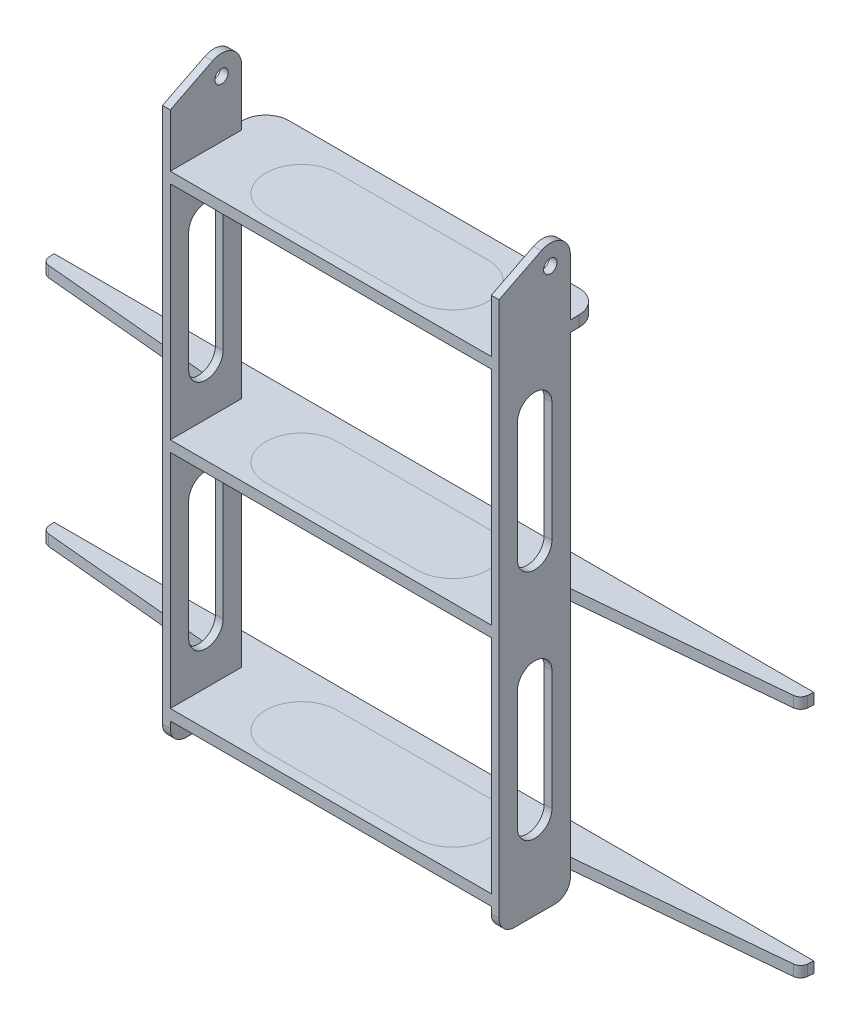
SolidWorks part; units mm, degrees
ref_plane "Front Plane" through (0, 0, 0) normal (0, 0, 1) x (1, 0, 0)
ref_plane "Top Plane" through (0, 0, 0) normal (0, 1, 0) x (1, 0, 0)
ref_plane "Right Plane" through (0, 0, 0) normal (1, 0, 0) x (0, 0, -1)
sketch "Sketch1" plane through (0, 0, 0) normal (0, 0, 1) x (1, 0, 0)
  line L1 (618.735, 7) -> (-618.735, 7)
  line L2 (618.735, 7) -> (618.735, -7)
  line L3 (618.735, -7) -> (-618.735, -7)
  line L4 (-618.735, 7) -> (-618.735, -7)
  line L5 (618.735, 7) -> (-618.735, -7) construction
  line L6 (618.735, -7) -> (-618.735, 7) construction
  point P0 (0, 0)
  dimension "D1" = 14
  dimension "D2" = 1237.47
extrude "Boss-Extrude1" add sketch "Sketch1" along normal blind 133
pattern_linear "LPattern1" count 3 spacing 300 along (0, -1, 0) of bodies 101
sketch "Sketch2" plane through (0, 7, 0) normal (0, 1, 0) x (1, 0, 0)
  line L0 (-675.1748, 0) -> (-675.1748, -133)
  line L1 (-675.1748, -133) -> (-217.0071, -133)
  line L2 (-217.0071, -133) -> (-217.0071, -41.0381)
  line L3 (-217.0071, -41.0381) -> (-488.6419, -15.7437)
  line L4 (-488.6419, -15.7437) -> (-489.975, 0)
  line L5 (-489.975, 0) -> (-675.1748, 0)
  line L6 (618.735, 0) -> (-618.735, 0) construction
  line L7 (618.735, -133) -> (-618.735, -133) construction
  line L8 (-618.735, -133) -> (-618.735, 0) construction
  line L9 (0, 0) -> (0, -201.9919) construction
  line L10 (489.975, 0) -> (675.1748, 0)
  line L11 (488.6419, -15.7437) -> (489.975, 0)
  line L12 (217.0071, -41.0381) -> (488.6419, -15.7437)
  line L13 (217.0071, -133) -> (217.0071, -41.0381)
  line L14 (675.1748, -133) -> (217.0071, -133)
  line L15 (675.1748, 0) -> (675.1748, -133)
  dimension "D1" = 94.84
  dimension "D2" = 100.16
  dimension "D3" = 128.76
  dimension "D4" = 15.8
  dimension "D5" = 272.81
  dimension "D6" = 401.7279
extrude "Cut-Extrude1" cut sketch "Sketch2" against normal through all both and the other way through all
sketch "Sketch3" plane through (-217.0071, 0, 0) normal (-1, 0, 0) x (0, 0, 1)
  line L0 (41.0381, -307) -> (41.0381, -293) construction
  line L1 (41.0381, 105.76) -> (133, 105.76)
  line L2 (41.0381, 105.76) -> (41.0381, -635.5)
  line L3 (41.0381, -635.5) -> (133, -635.5)
  line L4 (133, 105.76) -> (133, -635.5)
  line L5 (133, -293) -> (133, -307) construction
  line L6 (41.0381, 7) -> (133, 7) construction
  line L7 (133, -607) -> (41.0381, -607) construction
  dimension "D1" = 98.76
  dimension "D2" = 28.5
extrude "Boss-Extrude2" add sketch "Sketch3" against normal blind 10
mirror "Mirror1" about plane through (0, 0, 0) normal (1, 0, 0) of "Boss-Extrude2"
sketch "Sketch4" plane through (0, 7, 0) normal (0, 1, 0) x (1, 0, 0)
  line L0 (-217.0071, -133) -> (-217.0071, -41.0381) construction
  line L1 (-217.0071, 143.9317) -> (-506.9137, 143.9317)
  line L2 (-217.0071, 143.9317) -> (-217.0071, -232.2022)
  line L3 (-217.0071, -232.2022) -> (-506.9137, -232.2022)
  line L4 (-506.9137, 143.9317) -> (-506.9137, -232.2022)
  line L5 (0, -174.1148) -> (0, -390.7884) construction
  line L6 (217.0071, -232.2022) -> (506.9137, -232.2022)
  line L7 (506.9137, 143.9317) -> (506.9137, -232.2022)
  line L8 (217.0071, 143.9317) -> (506.9137, 143.9317)
  line L9 (217.0071, 143.9317) -> (217.0071, -232.2022)
  point P13 (0, -174.1148)
extrude "Cut-Extrude3" cut sketch "Sketch4" against normal blind 105
sketch "Sketch5" plane through (217.0071, 0, 0) normal (1, 0, 0) x (0, 0, -1)
  line L0 (-41.0381, -7) -> (-41.0381, -293) construction
  line L1 (-133, 105.76) -> (-41.0381, 105.76) construction
  line L2 (-133, 75.48) -> (-78.5502, 102.9795)
  line L3 (-66.8981, 79.9) -> (-78.5502, 102.9795) construction
  line L4 (-133, -635.5) -> (-133, 105.76) construction
  line L5 (-41.0381, 105.76) -> (-41.0381, 7) construction
  line L6 (-66.8981, 79.9) -> (-41.0381, 79.9) construction
  line L7 (-133, 75.48) -> (-161.3031, 75.48)
  line L8 (-161.3031, 75.48) -> (-161.3031, 131.4565)
  line L9 (-161.3031, 131.4565) -> (-29.3032, 131.4565)
  line L10 (-29.3032, 131.4565) -> (-29.3032, 79.9)
  line L11 (-29.3032, 79.9) -> (-41.0381, 79.9)
  circle A0 centre (-66.8981, 79.9) radius 8.65
  arc A1 (-78.5502, 102.9795) -> (-41.0381, 79.9) centre (-66.8941, 79.9) cw
  point P11 (0, 0)
  point P12 (-133, 5.22)
  point P19 (0, 0)
  point P22 (-29.3032, 9.64)
  line M1 (-41.0381, 105.76) -> (-133, 105.76)
  line M2 (-133, 105.76) -> (-133, -635.5)
  line M12 (-41.0381, 7) -> (-41.0381, 105.76)
  dimension "D3" = 17.3
  dimension "D1" = 25.86
  dimension "D2" = 25.86
  dimension "D4" = 4.42
  dimension "D5" = 61
extrude "Cut-Extrude5" cut sketch "Sketch5" against normal through all both and the other way through all contours L2 A1 M12 M1 M2 | A0
fillet "Fillet1" radius 30 2 edges at (-217.0071, 0, 0) (217.0071, 0, 0)
fillet "Fillet2" radius 20 4 edges at (-212.0071, -635.5, 41.0381) (-212.0071, -635.5, 133) (212.0071, -635.5, 133) (212.0071, -635.5, 41.0381)
fillet "Fillet3" radius 10 4 edges at (-488.6419, -600, 15.7437) (-488.6419, -300, 15.7437) (488.6419, -600, 15.7437) (488.6419, -300, 15.7437)
sketch "Sketch6" plane through (-217.0071, 0, 0) normal (-1, 0, 0) x (0, 0, 1)
  line L0 (87.0191, -635.5) -> (87.0191, 140.949) construction
  line L1 (61.0381, -635.5) -> (113, -635.5) construction
  line L2 (87.0191, -73.05) -> (87.0191, -226.95) construction
  line L3 (109.2491, -73.05) -> (109.2491, -226.95)
  line L4 (64.7891, -73.05) -> (64.7891, -226.95)
  line L5 (87.0191, -373.05) -> (87.0191, -526.95) construction
  line L6 (109.2491, -373.05) -> (109.2491, -526.95)
  line L7 (64.7891, -373.05) -> (64.7891, -526.95)
  line L8 (41.0381, -150) -> (133, -150) construction
  line L9 (41.0381, -7) -> (41.0381, -293) construction
  line L10 (133, 75.48) -> (133, -615.5) construction
  line L11 (41.0381, -450) -> (133, -450) construction
  line L12 (41.0381, -307) -> (41.0381, -593) construction
  arc A0 (109.2491, -73.05) -> (64.7891, -73.05) centre (87.0191, -73.05) ccw
  arc A1 (64.7891, -226.95) -> (109.2491, -226.95) centre (87.0191, -226.95) ccw
  arc A2 (109.2491, -373.05) -> (64.7891, -373.05) centre (87.0191, -373.05) ccw
  arc A3 (64.7891, -526.95) -> (109.2491, -526.95) centre (87.0191, -526.95) ccw
  point P6 (87.0191, -150)
  point P11 (87.0191, -450)
  point P18 (0, 0)
  dimension "D2" = 22.23
  dimension "D1" = 153.9
extrude "Cut-Extrude6" cut sketch "Sketch6" against normal through all both and the other way through all
sketch "Sketch7" plane through (0, 7, 0) normal (0, 1, 0) x (1, 0, 0)
  line L0 (-97.5, -73.3621) -> (97.5, -73.3621) construction
  line L1 (-97.5, -27.3621) -> (97.5, -27.3621)
  line L2 (-97.5, -119.3621) -> (97.5, -119.3621)
  arc A0 (-97.5, -27.3621) -> (-97.5, -119.3621) centre (-97.5, -73.3621) ccw
  arc A1 (97.5, -119.3621) -> (97.5, -27.3621) centre (97.5, -73.3621) ccw
  point P2 (0, -73.3621)
  point P7 (0, 0)
  dimension "D2" = 46
  dimension "D1" = 195
split line "Split Line1"
